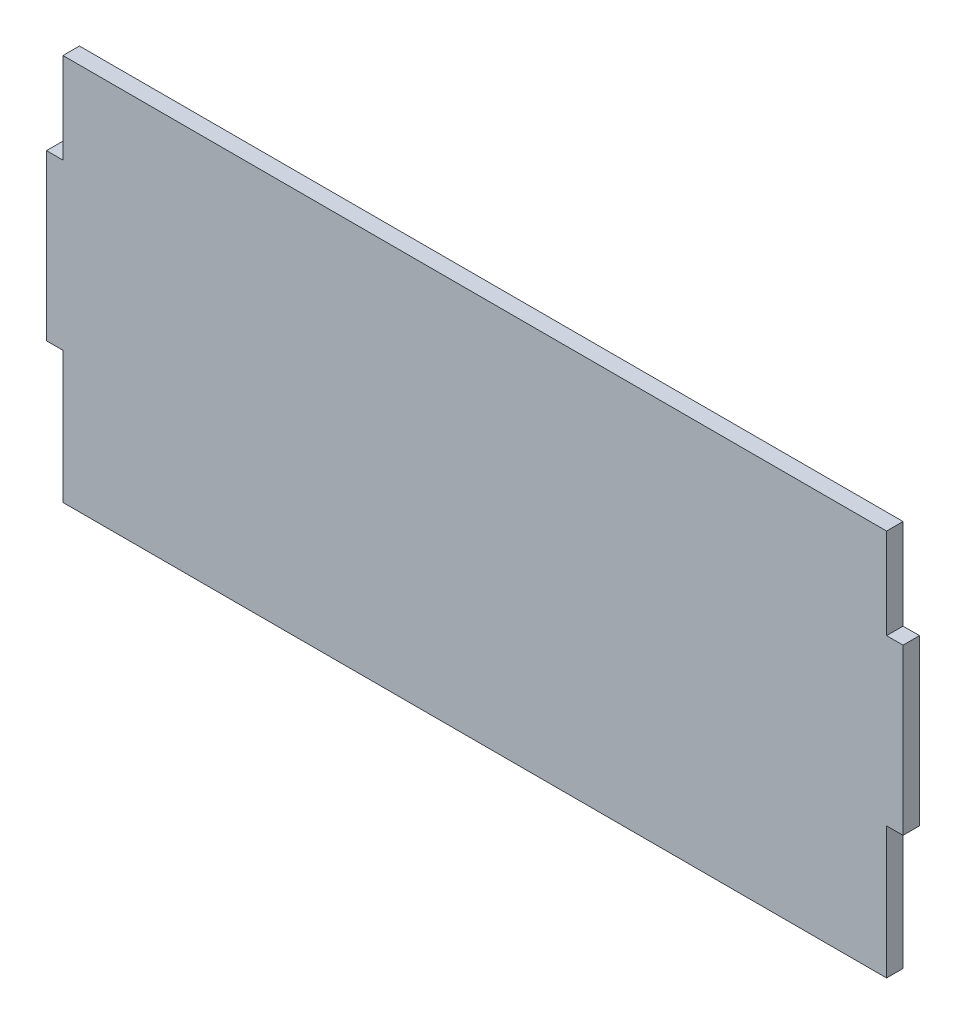
SolidWorks part; units mm, degrees
ref_plane "Спереди" through (0, 0, 0) normal (0, 0, 1) x (1, 0, 0)
ref_plane "Сверху" through (0, 0, 0) normal (0, 1, 0) x (1, 0, 0)
ref_plane "Справа" through (0, 0, 0) normal (1, 0, 0) x (0, 0, -1)
sketch "Эскиз1" plane through (0, 0, 0) normal (0, 0, 1) x (1, 0, 0)
  line L1 (0, 0) -> (100, 0)
  line L2 (0, 0) -> (0, 47)
  line L3 (0, 47) -> (100, 47)
  line L4 (100, 0) -> (100, 47)
  line L5 (100, 36) -> (102, 36)
  line L6 (100, 36) -> (100, 16)
  line L7 (100, 16) -> (102, 16)
  line L8 (102, 36) -> (102, 16)
  line L9 (0, 36) -> (-2, 36)
  line L10 (0, 36) -> (0, 16)
  line L11 (0, 16) -> (-2, 16)
  line L12 (-2, 36) -> (-2, 16)
  point P13 (103.1927, 11.333)
  point P14 (-8.9267, 20.1819)
  point P15 (0, 23.5)
  dimension "D1" = 100
  dimension "D2" = 47
  dimension "D3" = 11
  dimension "D4" = 11
  dimension "D5" = 20
  dimension "D6" = 20
  dimension "D7" = 2
  dimension "D8" = 2
extrude "Бобышка-Вытянуть1" add sketch "Эскиз1" along normal blind 2 contours L8 L5 L4 L7 | L1 L4 L3 L2 | L12 L11 L10 L9
